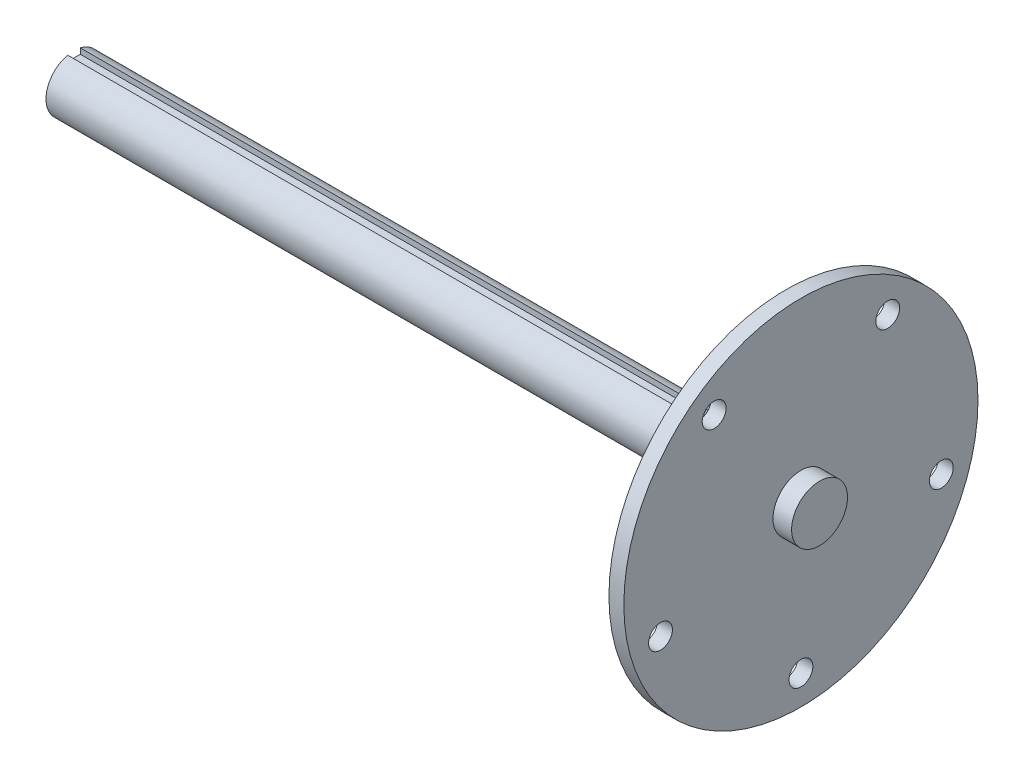
SolidWorks part; units mm, degrees
material "Alloy Steel"
ref_plane "Front Plane" through (0, 0, 0) normal (0, 0, 1) x (1, 0, 0)
ref_plane "Top Plane" through (0, 0, 0) normal (0, 1, 0) x (1, 0, 0)
ref_plane "Right Plane" through (0, 0, 0) normal (1, 0, 0) x (0, 0, -1)
sketch "Sketch1" plane through (0, 0, 0) normal (1, 0, 0) x (0, 0, -1)
  line L0 (0, 0) -> (0, -50.292) construction
  line L1 (0, 0) -> (-47.8305, -15.5411) construction
  circle A0 centre (0, 0) radius 60.325
  circle A1 centre (0, 0) radius 50.292 construction
  circle A2 centre (0, -50.292) radius 4.064
  circle A3 centre (-47.8305, -15.5411) radius 4.064
  circle A4 centre (-29.5609, 40.6871) radius 4.064
  circle A5 centre (29.5609, 40.6871) radius 4.064
  circle A6 centre (47.8305, -15.5411) radius 4.064
  point P16 (0, 0)
  dimension "D1" = 120.65
  dimension "D2" = 100.584
  dimension "D3" = 8.128
  dimension "D4" = 72
extrude "Boss-Extrude1" add sketch "Sketch1" along normal blind 5.08
sketch "Sketch2" plane through (5.08, 0, 0) normal (1, 0, 0) x (0, 0, -1)
  circle A0 centre (0, 0) radius 9.525
  dimension "D1" = 19.05
extrude "Boss-Extrude2" add sketch "Sketch2" along normal blind 6.35 and the other way blind 247.65
sketch "Sketch4" plane through (-242.57, 0, 0) normal (-1, 0, 0) x (0, 0, 1)
  line L1 (2.159, 7.375) -> (-2.159, 7.375)
  line L2 (2.159, 7.375) -> (2.159, 9.525)
  line L3 (2.159, 9.525) -> (-2.159, 9.525)
  line L4 (-2.159, 7.375) -> (-2.159, 9.525)
  circle A0 centre (0, 0) radius 9.525 construction
  point P6 (0, 7.375)
  dimension "D1" = 4.318
  dimension "D2" = 2.15
extrude "Cut-Extrude1" cut sketch "Sketch4" against normal offset from surface (228.6 mm away) 25.4 up to face at (11.43, 0, -9.525)
